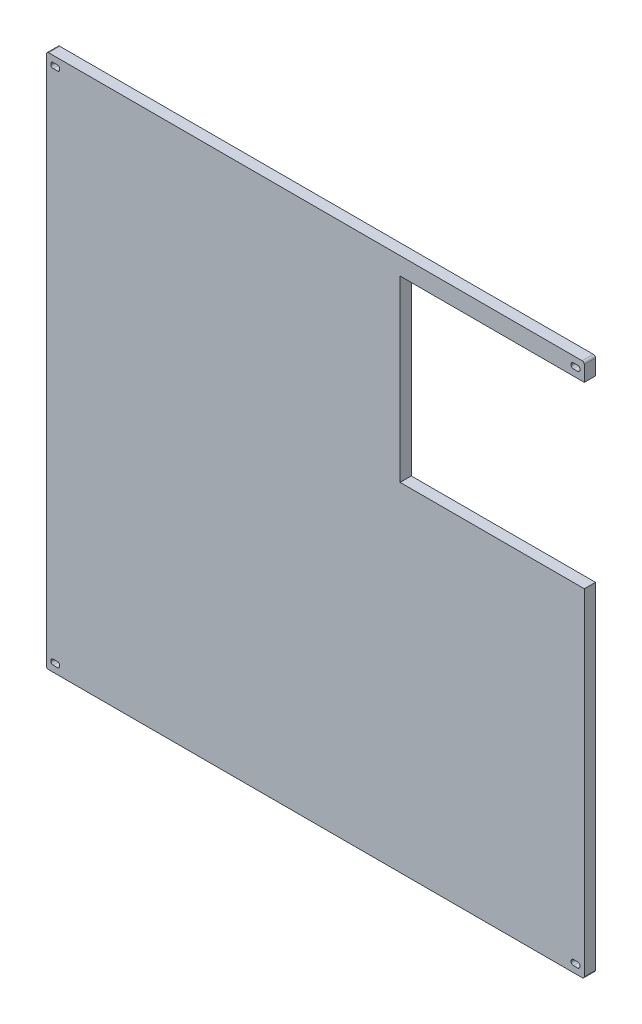
SolidWorks part; units mm, degrees
ref_plane "Front Plane" through (0, 0, 0) normal (0, 0, 1) x (1, 0, 0)
ref_plane "Top Plane" through (0, 0, 0) normal (0, 1, 0) x (1, 0, 0)
ref_plane "Right Plane" through (0, 0, 0) normal (1, 0, 0) x (0, 0, -1)
sketch "Sketch1" plane through (0, 0, 0) normal (0, 0, 1) x (1, 0, 0)
  line L0 (-5, 10.5) -> (-5, 9.5)
  line L1 (0, 0) -> (-611.632, 0)
  line L2 (0, 0) -> (0, 384.2809)
  line L3 (0, 607.568) -> (-611.632, 607.568)
  line L4 (-611.632, 0) -> (-611.632, 607.568)
  line L5 (0, 587.4809) -> (0, 607.568)
  line L6 (0, 587.4809) -> (-209.5191, 587.4809)
  line L8 (0, 384.2809) -> (-209.5191, 384.2809)
  line L9 (-209.5191, 587.4809) -> (-209.5191, 384.2809)
  line L10 (-7.5, 13) -> (-12.5, 13)
  line L11 (-15, 10.5) -> (-15, 9.5)
  line L12 (-7.5, 7) -> (-12.5, 7)
  line L13 (-10, 13) -> (-10, 7) construction
  line L14 (-15, 10) -> (-5, 10) construction
  line L15 (-596.63, 10.5) -> (-596.63, 9.5)
  line L16 (-599.13, 7) -> (-604.13, 7)
  line L17 (-606.63, 10.5) -> (-606.63, 9.5)
  line L18 (-599.13, 13) -> (-604.13, 13)
  line L19 (-596.63, 598.07) -> (-596.63, 597.07)
  line L20 (-599.13, 594.57) -> (-604.13, 594.57)
  line L21 (-606.63, 598.07) -> (-606.63, 597.07)
  line L22 (-599.13, 600.57) -> (-604.13, 600.57)
  line L23 (-5, 598.07) -> (-5, 597.07)
  line L24 (-7.5, 594.57) -> (-12.5, 594.57)
  line L25 (-15, 598.07) -> (-15, 597.07)
  line L26 (-7.5, 600.57) -> (-12.5, 600.57)
  line L27 (-209.5191, 641.3) -> (-209.5191, 384.2809) construction
  arc A0 (-5, 10.5) -> (-7.5, 13) centre (-7.5, 10.5) ccw
  arc A1 (-12.5, 13) -> (-15, 10.5) centre (-12.5, 10.5) ccw
  arc A2 (-5, 9.5) -> (-7.5, 7) centre (-7.5, 9.5) cw
  arc A3 (-15, 9.5) -> (-12.5, 7) centre (-12.5, 9.5) ccw
  arc A4 (-596.63, 9.5) -> (-599.13, 7) centre (-599.13, 9.5) cw
  arc A5 (-606.63, 9.5) -> (-604.13, 7) centre (-604.13, 9.5) ccw
  arc A6 (-604.13, 13) -> (-606.63, 10.5) centre (-604.13, 10.5) ccw
  arc A7 (-596.63, 10.5) -> (-599.13, 13) centre (-599.13, 10.5) ccw
  arc A8 (-596.63, 597.07) -> (-599.13, 594.57) centre (-599.13, 597.07) cw
  arc A9 (-606.63, 597.07) -> (-604.13, 594.57) centre (-604.13, 597.07) ccw
  arc A10 (-604.13, 600.57) -> (-606.63, 598.07) centre (-604.13, 598.07) ccw
  arc A11 (-596.63, 598.07) -> (-599.13, 600.57) centre (-599.13, 598.07) ccw
  arc A12 (-5, 597.07) -> (-7.5, 594.57) centre (-7.5, 597.07) cw
  arc A13 (-15, 597.07) -> (-12.5, 594.57) centre (-12.5, 597.07) ccw
  arc A14 (-12.5, 600.57) -> (-15, 598.07) centre (-12.5, 598.07) ccw
  arc A15 (-5, 598.07) -> (-7.5, 600.57) centre (-7.5, 598.07) ccw
  dimension "D4" = 2.5
  dimension "D1" = 611.632
  dimension "D2" = 607.568
  dimension "D3" = 6
  dimension "D5" = 10
  dimension "D6" = 10
  dimension "D7" = 2
  dimension "D8" = 2
  dimension "1000" = 10
  dimension "D9" = 5
  dimension "D10" = 6.998
  dimension "D11" = 5.002
  dimension "D12" = 384.2809
  dimension "D13" = 203.2
extrude "Boss-Extrude2" add sketch "Sketch1" along normal blind 12.7
fillet "Fillet2" radius 2.5 4 edges at (-611.632, 0, 6.35) (0, 0, 6.35) (-611.632, 607.568, 6.35) (0, 607.568, 6.35)
